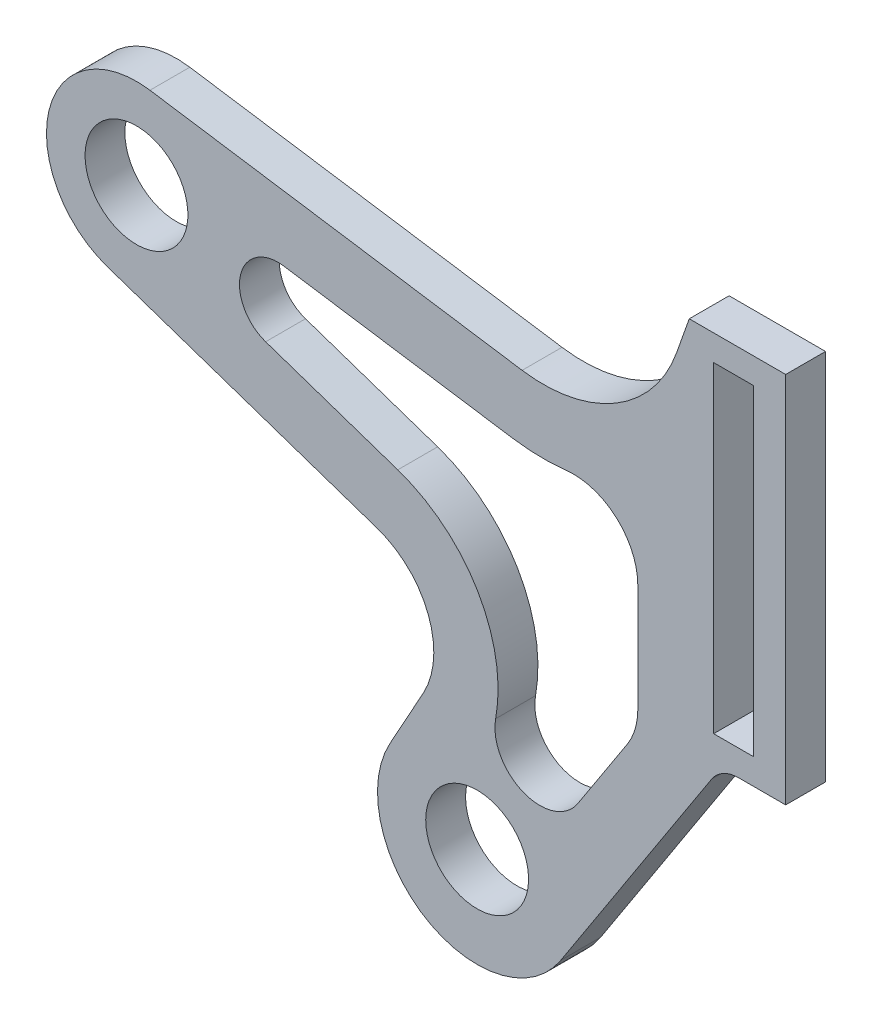
SolidWorks part; units mm, degrees
ref_plane "Front Plane" through (0, 0, 0) normal (0, 0, 1) x (1, 0, 0)
ref_plane "Top Plane" through (0, 0, 0) normal (0, 1, 0) x (1, 0, 0)
ref_plane "Right Plane" through (0, 0, 0) normal (1, 0, 0) x (0, 0, -1)
sketch "Sketch1" plane through (0, 0, 0) normal (0, 0, 1) x (1, 0, 0)
  line L52 (31.0361, 82.459) -> (33, 88)
  line L53 (33, 88) -> (48, 88)
  line L54 (48, 88) -> (48, 30)
  line L55 (48, 30) -> (40.6749, 30)
  line L59 (36.8, 34) -> (43, 34)
  line L60 (43, 34) -> (43, 84)
  line L61 (43, 84) -> (36.8, 84)
  line L62 (36.8, 84) -> (36.8, 34)
  line L63 (-57.5, 49.7429) -> (-15.5618, 35.5074)
  line L64 (-50.9, 76.8416) -> (7, 68.0572)
  line L65 (36.4814, 27.7229) -> (13, -8.441)
  line L66 (-13.5647, 7.5) -> (-8.3635, 16.9069)
  line L67 (-30.0733, 63.5674) -> (5.5, 58.1704)
  line L68 (25, 48.0721) -> (25, 31.3649)
  line L69 (-32.9018, 51.9537) -> (-12.3475, 44.9767)
  line L70 (23.3871, 25.9191) -> (15.6415, 13.9901)
  line L71 (28.0943, 33.1687) -> (4.6129, -2.9952) construction
  line L72 (-52.4, 66.9547) -> (5.5, 58.1704) construction
  line L73 (-54.2857, 59.2123) -> (-12.3475, 44.9767) construction
  circle A0 centre (0, 0) radius 5.075
  circle A1 centre (-53, 63) radius 8
  circle A2 centre (0, 0) radius 8
  arc A17 (-50.9, 76.8416) -> (-57.5, 49.7429) centre (-53, 63) ccw
  arc A18 (7, 68.0572) -> (31.0361, 82.459) centre (10.3, 89.8083) ccw
  arc A19 (40.6749, 30) -> (36.4814, 27.7229) centre (40.6749, 25) ccw
  arc A20 (-13.5647, 7.5) -> (13, -8.441) centre (0, 0) ccw
  arc A21 (-8.3635, 16.9069) -> (-15.5618, 35.5074) centre (-19.7403, 23.1972) ccw
  arc A22 (5.5, 58.1704) -> (13.881, 58.0093) centre (10.3, 89.8083) ccw
  arc A23 (2.8847, 19.061) -> (-12.3475, 44.9767) centre (-19.7403, 23.1972) ccw
  arc A25 (-30.0733, 63.5674) -> (-32.9018, 51.9537) centre (-30.9733, 57.6353) ccw
  arc A26 (25, 31.3649) -> (23.3871, 25.9191) centre (15, 31.3649) cw
  arc A27 (5.5, 58.1704) -> (40.4616, 79.1183) centre (10.3, 89.8083) ccw construction
  arc A28 (13.881, 58.0093) -> (25, 48.0721) centre (15, 48.0721) cw
  arc A29 (2.8847, 19.061) -> (15.6415, 13.9901) centre (9.7706, 17.8021) ccw
  arc A30 (0.3879, 12.0682) -> (-12.3475, 44.9767) centre (-19.7403, 23.1972) ccw construction
  point P21 (43, 59)
  point P27 (48, 59)
  dimension "D1" = 15.5
  dimension "D3" = 10.15
  dimension "D4" = 16
  dimension "D5" = 16
  dimension "D7" = 63
  dimension "D6" = 13
  dimension "D8" = 53
  dimension "D17" = 30
  dimension "D18" = 5
  dimension "D19" = 22
  dimension "D20" = 60
  dimension "D24" = 10
  dimension "D25" = 7
  dimension "D26" = 25
  dimension "D27" = 6
  dimension "D9" = 14
  dimension "D12" = 2.1
  dimension "D13" = 5
  dimension "D16" = 48
  dimension "D10" = 4.5
  dimension "D11" = 7.5
  dimension "D14" = 58
  dimension "D15" = 13
  dimension "D28" = 6.2
  dimension "D29" = 50
  dimension "D30" = 15
  dimension "D21" = 10
  dimension "D22" = 10
  dimension "D23" = 10
extrude "Boss-Extrude1" add sketch "Sketch1" along normal blind 6.2
